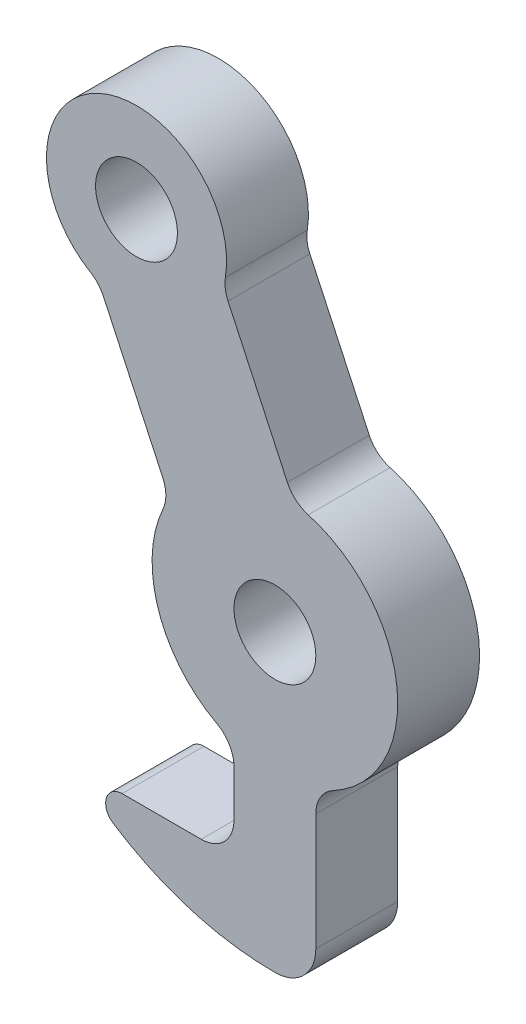
SolidWorks part; units mm, degrees
ref_plane "Front Plane" through (0, 0, 0) normal (0, 0, 1) x (1, 0, 0)
ref_plane "Top Plane" through (0, 0, 0) normal (0, 1, 0) x (1, 0, 0)
ref_plane "Right Plane" through (0, 0, 0) normal (1, 0, 0) x (0, 0, -1)
sketch "Sketch1" plane through (0, 0, 0) normal (0, 0, 1) x (1, 0, 0)
  line L0 (1.4992, 9.4063) -> (-3.9943, 21.1872)
  line L1 (-8.1693, 4.8978) -> (-13.6628, 16.6787)
  line L3 (3.175, -8.9803) -> (3.175, -19.685)
  line L4 (0, 0) -> (-10.7345, 23.0202) construction
  line L7 (0, -19.685) -> (0, 0) construction
  line L9 (-3.175, -8.9803) -> (-3.175, -16.7736)
  line L11 (-12.9813, -16.7736) -> (-15.5314, -16.7736) construction
  line L12 (-3.175, -16.7736) -> (-15.5314, -16.7736)
  arc A0 (3.175, -8.9803) -> (1.4992, 9.4063) centre (0, 0) ccw
  circle A1 centre (-10.7345, 23.0202) radius 3.175
  arc A2 (0, -22.86) -> (3.175, -19.685) centre (0, -19.685) ccw
  arc A3 (-3.9943, 21.1872) -> (-13.6628, 16.6787) centre (-10.7345, 23.0202) ccw
  circle A4 centre (0, 0) radius 3.175
  arc A6 (-8.1693, 4.8978) -> (-3.175, -8.9803) centre (0, 0) ccw
  arc A7 (0, -22.86) -> (-15.5314, -16.7736) centre (0, 0) cw
  dimension "D1" = 6.35
  dimension "D3" = 6.35
  dimension "D4" = 19.05
  dimension "D5" = 13.97
  dimension "D7" = 22.86
  dimension "D2" = 6.35
  dimension "D6" = 10.668
  dimension "D8" = 25.4
extrude "Boss-Extrude1" add sketch "Sketch1" along normal mid plane 6.35
fillet "Fillet1" radius 2.54 7 edges at (-3.9943, 21.1872, 0) (-13.6628, 16.6787, 0) (-8.1693, 4.8978, 0) (1.4992, 9.4063, 0) (3.175, -8.9803, 0) (-3.175, -8.9803, 0) (-3.175, -16.7736, 0)
fillet "Fillet2" radius 1.27 1 edges at (-15.5314, -16.7736, 0)
